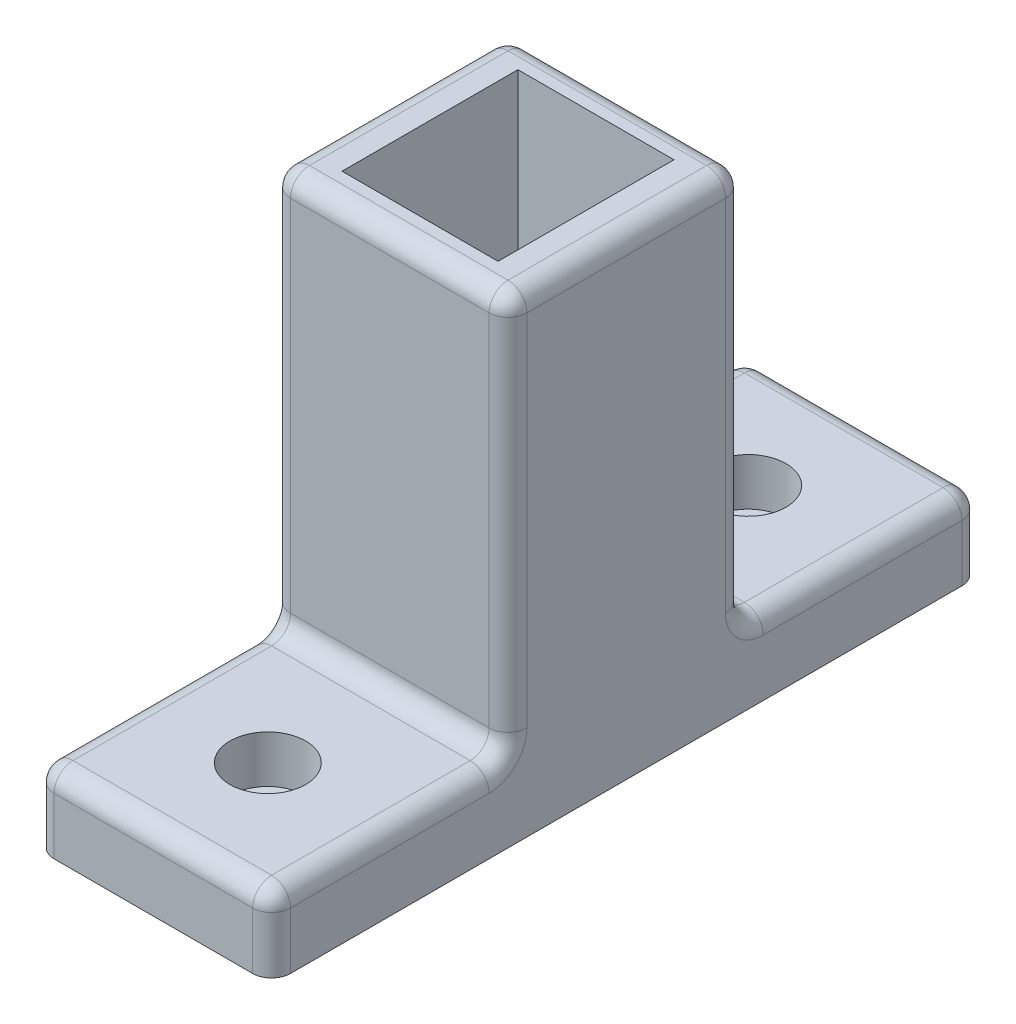
SolidWorks part; units mm, degrees
material "ABS"
ref_plane "Front Plane" through (0, 0, 0) normal (0, 0, 1) x (1, 0, 0)
ref_plane "Top Plane" through (0, 0, 0) normal (0, 1, 0) x (1, 0, 0)
ref_plane "Right Plane" through (0, 0, 0) normal (1, 0, 0) x (0, 0, -1)
sketch "Sketch1" plane through (0, 0, 0) normal (0, 1, 0) x (1, 0, 0)
  line L1 (-8.25, -9.3) -> (8.25, -9.3)
  line L2 (-8.25, -9.3) -> (-8.25, 9.3)
  line L3 (-8.25, 9.3) -> (8.25, 9.3)
  line L4 (8.25, -9.3) -> (8.25, 9.3)
  line L5 (-8.25, -9.3) -> (8.25, 9.3) construction
  line L6 (-8.25, 9.3) -> (8.25, -9.3) construction
  line L7 (-12.5, -12.5) -> (12.5, -12.5)
  line L8 (-12.5, -12.5) -> (-12.5, 12.5)
  line L9 (-12.5, 12.5) -> (12.5, 12.5)
  line L10 (12.5, -12.5) -> (12.5, 12.5)
  line L11 (-12.5, -12.5) -> (12.5, 12.5) construction
  line L12 (-12.5, 12.5) -> (12.5, -12.5) construction
  point P0 (0, 0)
  point P6 (0, 0)
  dimension "D1" = 16.5
  dimension "D2" = 18.6
  dimension "D3" = 25
  dimension "D4" = 25
extrude "Boss-Extrude1" add sketch "Sketch1" along normal blind 50
sketch "Sketch6" plane through (0, 0, 0) normal (0, 1, 0) x (1, 0, 0)
  line L13 (-12.5, -37.5) -> (12.5, -37.5)
  line L14 (-12.5, -37.5) -> (-12.5, 37.5)
  line L15 (-12.5, 37.5) -> (12.5, 37.5)
  line L16 (12.5, -37.5) -> (12.5, 37.5)
  line L17 (-12.5, -37.5) -> (12.5, 37.5) construction
  line L18 (-12.5, 37.5) -> (12.5, -37.5) construction
  point P4 (0, 0)
  dimension "D5" = 75
  dimension "D6" = 25
extrude "Boss-Extrude3" add sketch "Sketch6" along normal blind 8
fillet "Fillet2" radius 2 20 edges at (0, 8, -12.5) (0, 50, -12.5) (12.5, 29, -12.5) (12.5, 50, 0) (12.5, 29, 12.5) (-12.5, 29, 12.5) (0, 50, 12.5) (-12.5, 29, -12.5) (-12.5, 50, 0) (-12.5, 8, -25) (12.5, 8, -25) (0, 8, -37.5) (0, 8, 37.5) (-12.5, 8, 25) (0, 8, 12.5) (12.5, 8, 25) (12.5, 4, -37.5) (-12.5, 4, -37.5) (12.5, 4, 37.5) (-12.5, 4, 37.5)
sketch "Sketch7" plane through (0, 8, 0) normal (0, 1, 0) x (1, 0, 0)
  line L0 (0, 0) -> (0, 25.4) construction
  line L1 (0, 0) -> (0, -25.4) construction
  circle A0 centre (0, 0) radius 4
  circle A1 centre (0, 25.4) radius 4
  circle A2 centre (0, -25.4) radius 4
extrude "Cut-Extrude1" cut sketch "Sketch7" against normal blind 5
sketch "Sketch8" plane through (0, 0, 0) normal (0, 1, 0) x (1, 0, 0)
  line L0 (0, 0) -> (0, 25.4) construction
  line L1 (0, 0) -> (0, -25.4) construction
  circle A0 centre (0, 0) radius 2.3813
  circle A1 centre (0, 25.4) radius 2.3813
  circle A2 centre (0, -25.4) radius 2.3813
extrude "Cut-Extrude4" cut sketch "Sketch8" against normal through all and the other way through all
